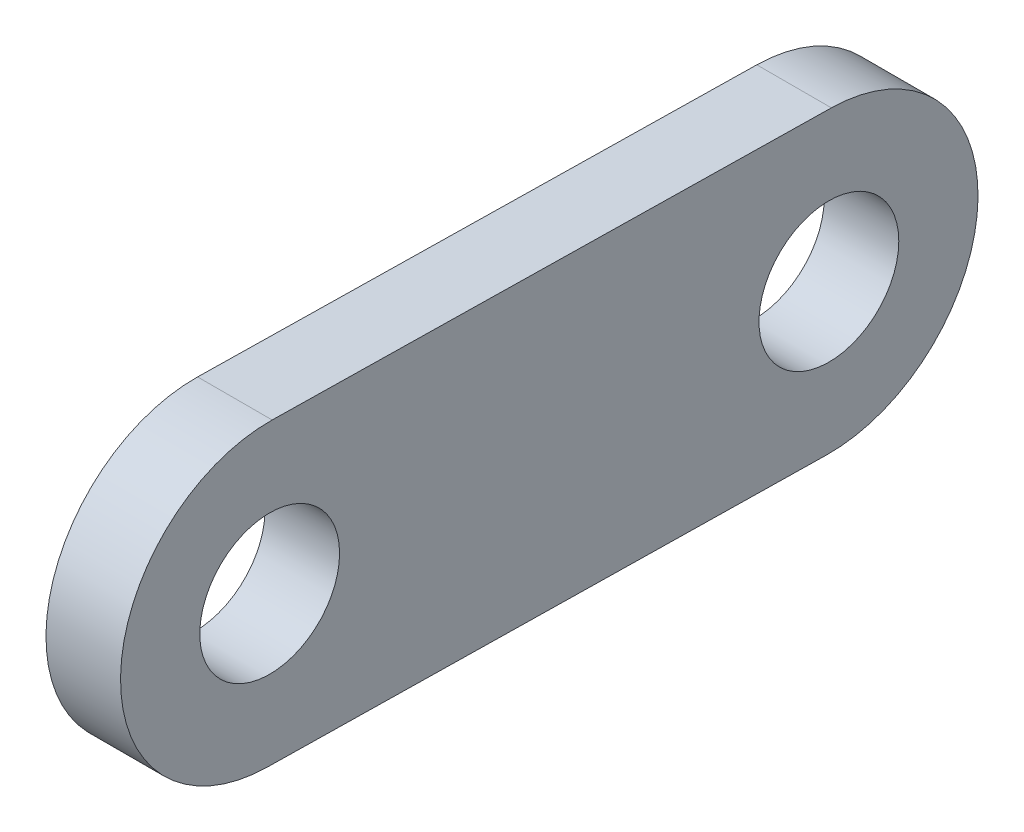
SolidWorks part; units mm, degrees
ref_plane "Front Plane" through (0, 0, 0) normal (0, 0, 1) x (1, 0, 0)
ref_plane "Top Plane" through (0, 0, 0) normal (0, 1, 0) x (1, 0, 0)
ref_plane "Right Plane" through (0, 0, 0) normal (1, 0, 0) x (0, 0, -1)
sketch "Sketch1" plane through (0, 0, 0) normal (1, 0, 0) x (0, 0, -1)
  line L0 (0, 0) -> (500, 0) construction
  line L1 (0, 0) -> (375, -6.25) construction
  line L2 (1.6664, 99.9861) -> (376.6664, 93.7361)
  line L3 (-1.6664, -99.9861) -> (373.3336, -106.2361)
  arc A0 (1.6664, 99.9861) -> (-1.6664, -99.9861) centre (0, 0) ccw
  arc A1 (373.3336, -106.2361) -> (376.6664, 93.7361) centre (375, -6.25) ccw
  circle A2 centre (0, 0) radius 46.875
  circle A3 centre (375, -6.25) radius 46.875
  point P3 (187.5, -3.125)
  dimension "D4" = 100
  dimension "D5" = 93.75
  dimension "D1" = 500
  dimension "D2" = 125
  dimension "D3" = 6.25
extrude "Boss-Extrude1" add sketch "Sketch1" along normal blind 50
